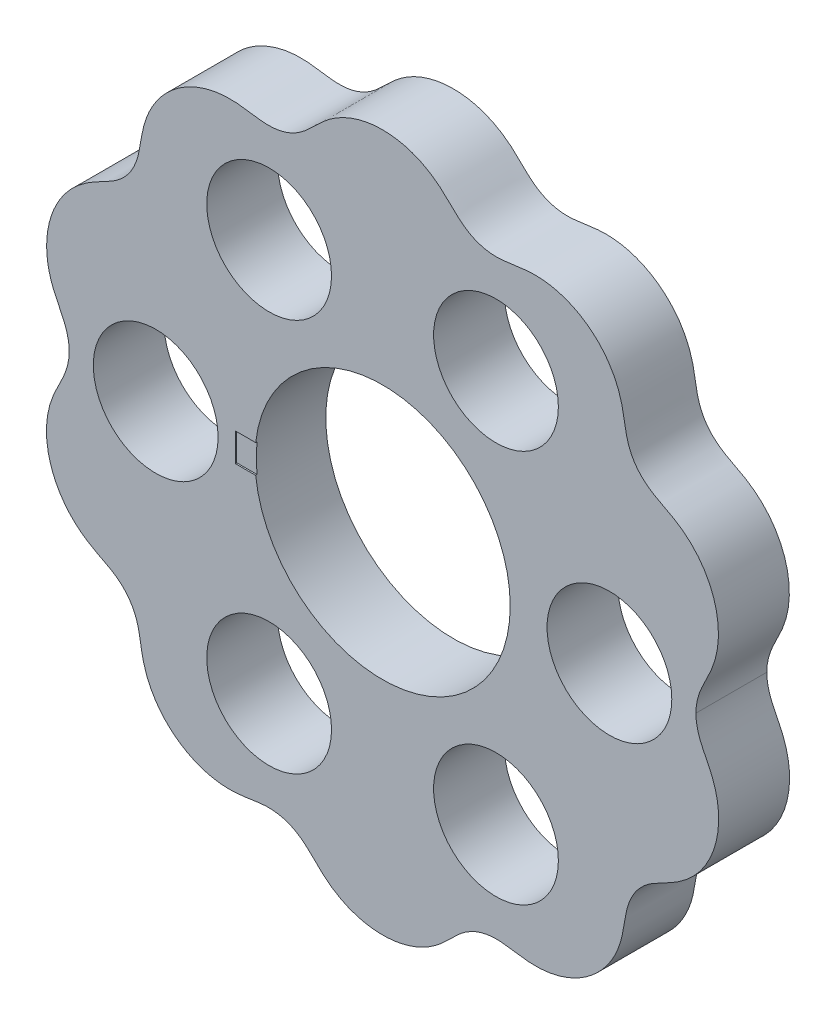
SolidWorks part; units mm, degrees
ref_plane "Front Plane" through (0, 0, 0) normal (0, 0, 1) x (1, 0, 0)
ref_plane "Top Plane" through (0, 0, 0) normal (0, 1, 0) x (1, 0, 0)
ref_plane "Right Plane" through (0, 0, 0) normal (1, 0, 0) x (0, 0, -1)
sketch "Sketch2" plane through (0, 0, 5.6053) normal (0, 0, 1) x (1, 0, 0)
  line L0 (0, 0) -> (16, 0) construction
  circle A1 centre (0, 0) radius 9.0043
  circle A2 centre (8, 13.8564) radius 4.4
  circle A3 centre (16, 0) radius 4.4
  circle A4 centre (8, -13.8564) radius 4.4
  circle A5 centre (-8, -13.8564) radius 4.4
  circle A6 centre (-16, 0) radius 4.4
  circle A7 centre (-8, 13.8564) radius 4.4
  spline S0 degree 4 poles (23.557, 7.0108) (23.5986, 6.8225) (23.6666, 6.4426) (23.7221, 5.8654) (23.7006, 5.0925) (23.5922, 4.3886) (23.4215, 3.7606) (23.2141, 3.209) (22.9937, 2.7289) (22.7529, 2.2591) (22.5466, 1.8458) (22.391, 1.4812) (22.2824, 1.1696) (22.2104, 0.9151) (22.1619, 0.6898) (22.1315, 0.4927) (22.1138, 0.3314) (22.1044, 0.199) (22.0995, 0.0431) (22.0996, -0.0366) (22.1028, -0.1505) (22.1078, -0.243) (22.113, -0.3136) (22.1212, -0.399) (22.1377, -0.5355) (22.1685, -0.7253) (22.222, -0.9617) (22.3011, -1.2285) (22.3962, -1.4893) (22.5046, -1.7453) (22.6227, -1.9965) (22.7467, -2.245) (22.8724, -2.4926) (22.9959, -2.7413) (23.1434, -3.0555) (23.3046, -3.4398) (23.4897, -3.9786) (23.651, -4.6834) (23.7301, -5.4867) (23.6901, -6.3763) (23.5267, -7.2454) (23.2469, -8.0784) (22.8584, -8.8593) (22.3699, -9.5758) (21.7468, -10.2595) (20.9798, -10.8802) (20.0719, -11.3935) (19.075, -11.857) (18.1814, -12.5254) (17.5226, -13.4352) (17.1659, -14.4991) (17.0352, -15.6021) (16.7731, -16.8502) (16.1832, -18.1698) (15.1853, -19.4264) (13.7589, -20.4568) (12.2578, -21.0093) (10.829, -21.1592) (9.5606, -21.0205) (8.461, -20.8021) (7.3284, -20.821) (6.2531, -21.1814) (5.3419, -21.8425) (4.5902, -22.6577) (3.6463, -23.5036) (2.4043, -24.213) (0.8726, -24.639) (-0.8726, -24.639) (-2.4043, -24.213) (-3.6463, -23.5036) (-4.5902, -22.6577) (-5.3419, -21.8425) (-6.2531, -21.1814) (-7.3284, -20.821) (-8.461, -20.8021) (-9.5606, -21.0205) (-10.829, -21.1592) (-12.2578, -21.0093) (-13.741, -20.4634) (-15.1394, -19.4615) (-16.0413, -18.3534) (-16.5535, -17.345) (-16.8193, -16.5384) (-16.9519, -15.9811) (-17.0719, -15.2755) (-17.1754, -14.568) (-17.3712, -13.8744) (-17.7598, -13.1055) (-18.3013, -12.4278) (-19.1201, -11.828) (-20.1618, -11.3541) (-21.2666, -10.702) (-22.3106, -9.734) (-23.1652, -8.4275) (-23.6256, -7.0174) (-23.7462, -5.7577) (-23.6634, -4.7771) (-23.5186, -4.0855) (-23.322, -3.4769) (-23.1003, -2.9486) (-22.8453, -2.4361) (-22.616, -1.991) (-22.4089, -1.5346) (-22.2772, -1.1634) (-22.2025, -0.8866) (-22.1548, -0.6409) (-22.1356, -0.5166) (-22.1225, -0.411) (-22.1138, -0.3229) (-22.1082, -0.2506) (-22.1041, -0.1747) (-22.1013, -0.0974) (-22.0996, -0.0136) (-22.1001, 0.0618) (-22.1044, 0.1995) (-22.1138, 0.3312) (-22.1315, 0.4927) (-22.1619, 0.6898) (-22.2104, 0.9151) (-22.2824, 1.1696) (-22.3693, 1.4188) (-22.4688, 1.6635) (-22.5782, 1.9037) (-22.6943, 2.1409) (-22.8135, 2.3764) (-22.9322, 2.6121) (-23.0764, 2.9089) (-23.2374, 3.2708) (-23.3876, 3.6703) (-23.5162, 4.109) (-23.627, 4.6149) (-23.7033, 5.1892) (-23.7194, 5.7688) (-23.6759, 6.3464) (-23.6156, 6.7276) (-23.5778, 6.9166) (-23.557, 7.0108) knots 0 0 0 0 0 0.00822 0.016439 0.024659 0.032878 0.038505 0.044131 0.049758 0.055384 0.061011 0.063824 0.066637 0.069451 0.072264 0.073671 0.075077 0.076484 0.077891 0.07937 0.08011 0.08085 0.08159 0.08233 0.08381 0.086769 0.089729 0.092688 0.095648 0.098607 0.101567 0.104526 0.107485 0.110445 0.113404 0.119323 0.125242 0.134701 0.144159 0.153617 0.163076 0.172284 0.181492 0.1907 0.199907 0.21162 0.223333 0.235045 0.246758 0.258596 0.270434 0.282272 0.294109 0.312776 0.331442 0.349816 0.36819 0.380136 0.392081 0.404027 0.415972 0.427792 0.439612 0.451432 0.463252 0.481626 0.5 0.518374 0.536748 0.548568 0.560388 0.572208 0.584028 0.595973 0.607919 0.619864 0.63181 0.650184 0.668558 0.686418 0.704279 0.710378 0.716478 0.722577 0.728677 0.740876 0.746976 0.753075 0.765274 0.777473 0.789672 0.801871 0.819732 0.837592 0.855453 0.864383 0.873313 0.879413 0.885512 0.891612 0.897711 0.903811 0.906861 0.91296 0.914485 0.91601 0.917535 0.918297 0.91906 0.919822 0.920585 0.921347 0.922109 0.923516 0.924923 0.926329 0.927736 0.930549 0.933363 0.936176 0.938989 0.941802 0.944616 0.947429 0.950242 0.953056 0.955869 0.961495 0.967122 0.971232 0.975341 0.983561 0.99178 0.99589 1 1 1 1 1 construction
  spline S1 degree 4 poles (22.1, 0) (22.1, -0.0293) (22.1007, -0.0733) (22.1028, -0.1505) (22.1078, -0.243) (22.113, -0.3136) (22.1212, -0.399) (22.1377, -0.5355) (22.1685, -0.7253) (22.222, -0.9617) (22.3011, -1.2285) (22.3962, -1.4893) (22.5046, -1.7453) (22.6227, -1.9965) (22.7467, -2.245) (22.8724, -2.4926) (22.9959, -2.7413) (23.1434, -3.0555) (23.3046, -3.4398) (23.4897, -3.9786) (23.651, -4.6834) (23.7301, -5.4867) (23.6901, -6.3763) (23.5267, -7.2454) (23.2469, -8.0784) (22.8584, -8.8593) (22.3699, -9.5758) (21.7468, -10.2595) (20.9798, -10.8802) (20.0719, -11.3935) (19.075, -11.857) (18.1814, -12.5254) (17.5226, -13.4352) (17.1659, -14.4991) (17.0352, -15.6021) (16.7731, -16.8502) (16.1832, -18.1698) (15.1853, -19.4264) (13.7589, -20.4568) (12.2578, -21.0093) (10.829, -21.1592) (9.5606, -21.0205) (8.461, -20.8021) (7.3284, -20.821) (6.2531, -21.1814) (5.3419, -21.8425) (4.5902, -22.6577) (3.6463, -23.5036) (2.4043, -24.213) (0.8726, -24.639) (-0.8726, -24.639) (-2.4043, -24.213) (-3.6463, -23.5036) (-4.5902, -22.6577) (-5.3419, -21.8425) (-6.2531, -21.1814) (-7.3284, -20.821) (-8.461, -20.8021) (-9.5606, -21.0205) (-10.829, -21.1592) (-12.2578, -21.0093) (-13.741, -20.4634) (-15.1394, -19.4615) (-16.0413, -18.3534) (-16.5535, -17.345) (-16.8193, -16.5384) (-16.9519, -15.9811) (-17.0719, -15.2755) (-17.1754, -14.568) (-17.3712, -13.8744) (-17.7598, -13.1055) (-18.3013, -12.4278) (-19.1201, -11.828) (-20.1618, -11.3541) (-21.2666, -10.702) (-22.3106, -9.734) (-23.1652, -8.4275) (-23.6256, -7.0174) (-23.7462, -5.7577) (-23.6634, -4.7771) (-23.5186, -4.0855) (-23.322, -3.4769) (-23.1003, -2.9486) (-22.8453, -2.4361) (-22.616, -1.991) (-22.4089, -1.5346) (-22.2772, -1.1634) (-22.2025, -0.8866) (-22.1548, -0.6409) (-22.1356, -0.5166) (-22.1225, -0.411) (-22.1138, -0.3229) (-22.1082, -0.2506) (-22.1041, -0.1747) (-22.1013, -0.0974) (-22.1002, -0.0455) (-22.1, -0.0151) (-22.1, 0) knots 0.077891 0.077891 0.077891 0.077891 0.077891 0.07937 0.08011 0.08085 0.08159 0.08233 0.08381 0.086769 0.089729 0.092688 0.095648 0.098607 0.101567 0.104526 0.107485 0.110445 0.113404 0.119323 0.125242 0.134701 0.144159 0.153617 0.163076 0.172284 0.181492 0.1907 0.199907 0.21162 0.223333 0.235045 0.246758 0.258596 0.270434 0.282272 0.294109 0.312776 0.331442 0.349816 0.36819 0.380136 0.392081 0.404027 0.415972 0.427792 0.439612 0.451432 0.463252 0.481626 0.5 0.518374 0.536748 0.548568 0.560388 0.572208 0.584028 0.595973 0.607919 0.619864 0.63181 0.650184 0.668558 0.686418 0.704279 0.710378 0.716478 0.722577 0.728677 0.740876 0.746976 0.753075 0.765274 0.777473 0.789672 0.801871 0.819732 0.837592 0.855453 0.864383 0.873313 0.879413 0.885512 0.891612 0.897711 0.903811 0.906861 0.91296 0.914485 0.91601 0.917535 0.918297 0.91906 0.919822 0.920585 0.921347 0.922109 0.922109 0.922109 0.922109 0.922109
  spline S2 degree 4 poles (22.1, 0) (22.1, 0.0149) (22.1002, 0.0449) (22.1012, 0.0961) (22.104, 0.1724) (22.108, 0.2475) (22.1135, 0.3191) (22.1219, 0.4061) (22.1347, 0.5104) (22.1534, 0.6332) (22.18, 0.7721) (22.2115, 0.9099) (22.2477, 1.0465) (22.2883, 1.1819) (22.3444, 1.3495) (22.4195, 1.5479) (22.5167, 1.7754) (22.6674, 2.0952) (22.859, 2.4734) (23.0785, 2.9169) (23.298, 3.4386) (23.4966, 4.046) (23.6456, 4.7431) (23.7141, 5.5267) (23.6709, 6.3853) (23.5126, 7.2261) (23.245, 8.0347) (22.8743, 8.7969) (22.4078, 9.5004) (21.8028, 10.1883) (21.0438, 10.8256) (20.1283, 11.364) (19.1016, 11.8388) (18.1812, 12.52) (17.5089, 13.455) (17.1558, 14.5438) (17.0233, 15.6668) (16.74, 16.913) (16.138, 18.2078) (15.1526, 19.4254) (13.9455, 20.2983) (12.7836, 20.7981) (11.6909, 21.052) (10.6988, 21.1285) (9.6298, 21.0305) (8.5029, 20.8049) (7.3425, 20.8147) (6.2381, 21.1848) (5.31, 21.8697) (4.5398, 22.7059) (3.5761, 23.5394) (2.3379, 24.2196) (0.8409, 24.6193) (-0.8409, 24.6193) (-2.3379, 24.2196) (-3.5761, 23.5394) (-4.5398, 22.7059) (-5.31, 21.8697) (-6.2381, 21.1848) (-7.3425, 20.8147) (-8.5029, 20.8049) (-9.6298, 21.0305) (-10.6988, 21.1285) (-11.6909, 21.052) (-12.7836, 20.7981) (-13.9398, 20.3008) (-15.1377, 19.4369) (-16.1216, 18.2307) (-16.7287, 16.9454) (-17.0198, 15.6974) (-17.1517, 14.562) (-17.5044, 13.46) (-18.1846, 12.5142) (-19.1175, 11.829) (-20.1564, 11.3515) (-21.2567, 10.6956) (-22.2973, 9.7268) (-23.1493, 8.4211) (-23.6091, 7.013) (-23.7306, 5.755) (-23.6496, 4.7756) (-23.5066, 4.0845) (-23.3122, 3.4761) (-23.1202, 3.0137) (-22.9351, 2.627) (-22.7749, 2.3077) (-22.6474, 2.0519) (-22.5096, 1.7614) (-22.3981, 1.4981) (-22.313, 1.2628) (-22.2508, 1.0577) (-22.2138, 0.9196) (-22.1817, 0.7803) (-22.1546, 0.6401) (-22.1355, 0.5159) (-22.1224, 0.4105) (-22.1137, 0.3225) (-22.1082, 0.2503) (-22.1041, 0.1745) (-22.1013, 0.0972) (-22.1002, 0.0454) (-22.1, 0.0151) (-22.1, 0) knots 0.077977 0.077977 0.077977 0.077977 0.077977 0.078731 0.079485 0.080239 0.080993 0.081747 0.082501 0.08401 0.085518 0.087026 0.088534 0.090042 0.09155 0.093059 0.096075 0.099091 0.102107 0.10814 0.114173 0.120205 0.126238 0.135381 0.144524 0.153668 0.162811 0.171787 0.180764 0.18974 0.198717 0.210782 0.222847 0.234912 0.246977 0.259042 0.271107 0.283172 0.295237 0.313357 0.331477 0.34922 0.358092 0.366964 0.37922 0.391477 0.403733 0.415989 0.42812 0.440251 0.452382 0.464513 0.482257 0.5 0.517743 0.535487 0.547618 0.559749 0.57188 0.584011 0.596267 0.608523 0.62078 0.633036 0.641908 0.65078 0.668523 0.68638 0.704237 0.716433 0.72863 0.740827 0.753023 0.76522 0.777416 0.789613 0.80181 0.819666 0.837523 0.85538 0.864308 0.873237 0.879335 0.885433 0.891531 0.894581 0.89763 0.900679 0.903728 0.908302 0.909826 0.911351 0.912876 0.9144 0.915925 0.917449 0.918212 0.918974 0.919736 0.920498 0.921261 0.922023 0.922023 0.922023 0.922023 0.922023
  point P22 (0, 0)
  dimension "D1" = 6
extrude "Boss-Extrude1" add sketch "Sketch2" against normal blind 5
sketch "Sketch3" plane through (0, 0, 5.6053) normal (0, 0, 1) x (1, 0, 0)
  line L0 (-9.0043, 0) -> (-10.3888, 0) construction
  line L1 (-10.3888, -1) -> (-10.3888, 1)
  line L2 (-10.3888, 1) -> (-8.7429, 1)
  line L3 (-10.3888, -1) -> (-8.6639, -1)
  line L4 (-8.6639, -1) -> (-8.6639, 1)
  line L5 (-8.6639, 1) -> (-8.7429, 1)
  circle A0 centre (0, 0) radius 9.0043 construction
extrude "Cut-Extrude1" cut sketch "Sketch3" against normal blind 0.1
